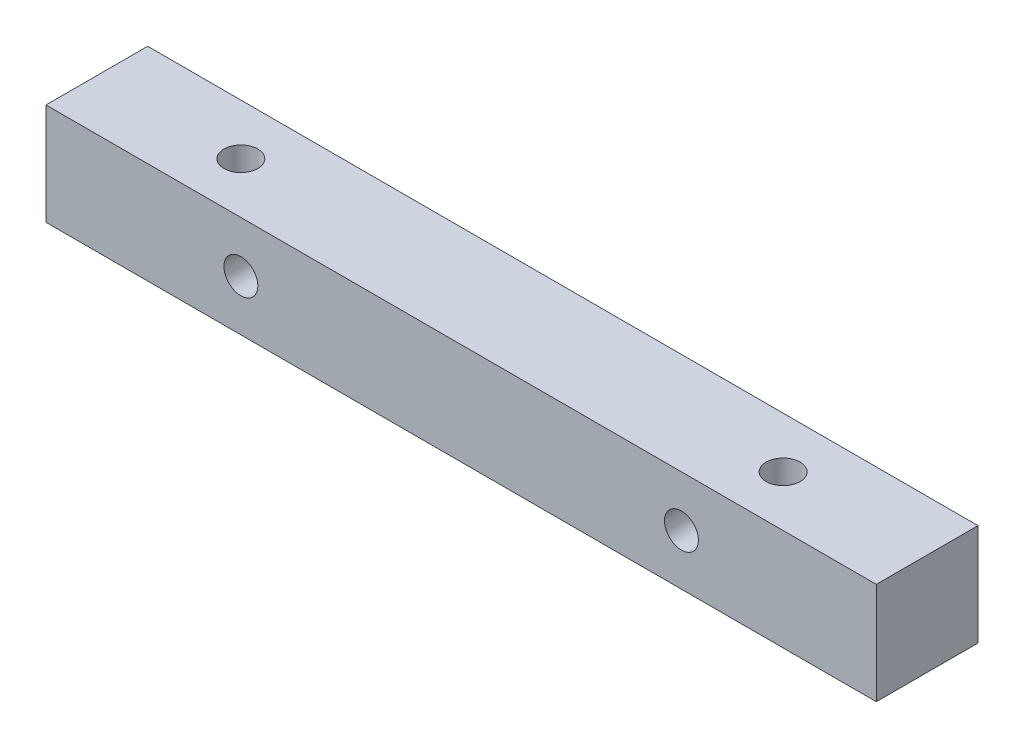
SolidWorks part; units mm, degrees
ref_plane "Front Plane" through (0, 0, 0) normal (0, 0, 1) x (1, 0, 0)
ref_plane "Top Plane" through (0, 0, 0) normal (0, 1, 0) x (1, 0, 0)
ref_plane "Right Plane" through (0, 0, 0) normal (1, 0, 0) x (0, 0, -1)
sketch "Sketch1" plane through (0, 0, 0) normal (1, 0, 0) x (0, 0, -1)
  line L0 (3, 3) -> (-3, -3) construction
  line L1 (-3, 3) -> (3, 3)
  line L2 (-3, 3) -> (-3, -3)
  line L3 (-3, -3) -> (3, -3)
  line L4 (3, 3) -> (3, -3)
  dimension "D1" = 6
extrude "Boss-Extrude1" add sketch "Sketch1" along normal blind 49
sketch "Sketch2" plane through (0, 0, 3) normal (0, 0, 1) x (1, 0, 0)
  line L0 (0, 0) -> (52.0188, 0) construction
  line L1 (24.5, 3) -> (24.5, -8.4198) construction
  line L2 (49, 3) -> (0, 3) construction
  point P0 (11.5, 0)
  point P1 (37.5, 0)
  dimension "D1" = 26
hole_wizard "Ø2.0mm Dowel Hole1" positions "3DSketch1" profile "Sketch3" hole size "Ø2.0" standard "ANSI Metric"
sketch3d "3DSketch1"
  point P0 (11.5, 0, 3)
  point P3 (37.5, 0, 3)
sketch "Sketch3" plane through (11.5, 0, 3) normal (1, 0, 0) x (0, -1, 0)
  line L0 (0, 0) -> (0, 10.6009)
  line L1 (0, 10.6009) -> (1, 10)
  line L2 (1, 10) -> (1, 0)
  line L5 (1, 0) -> (0, 0)
  line L10 (0, 10.6009) -> (-1, 10) construction
  line L11 (0, -6.35) -> (0, 107.95) construction
  dimension "Hole Dia." = 2
  dimension "Hole Depth" = 10
  dimension "Drill Angle" = 118
sketch "Sketch4" plane through (0, 3, 0) normal (0, 1, 0) x (1, 0, 0)
  line L0 (0, 0) -> (51.8712, 0) construction
  line L1 (24.5, 3) -> (24.5, -5.5023) construction
  line L2 (49, 3) -> (0, 3) construction
  point P7 (8.5, 0)
  point P8 (40.5, 0)
  dimension "D1" = 32
hole_wizard "Ø2.0mm Dowel Hole8" positions "3DSketch4" profile "Sketch7" hole size "Ø2.0" standard "ANSI Metric"
sketch3d "3DSketch4"
  point P0 (8.5, 3, 0)
  point P3 (40.5, 3, 0)
sketch "Sketch7" plane through (8.5, 3, 0) normal (1, 0, 0) x (0, 0, 1)
  line L0 (0, 0) -> (0, 10.6009)
  line L1 (0, 10.6009) -> (1, 10)
  line L2 (1, 10) -> (1, 0)
  line L5 (1, 0) -> (0, 0)
  line L10 (0, 10.6009) -> (-1, 10) construction
  line L11 (0, -6.35) -> (0, 107.95) construction
  dimension "Hole Dia." = 2
  dimension "Hole Depth" = 10
  dimension "Drill Angle" = 118
